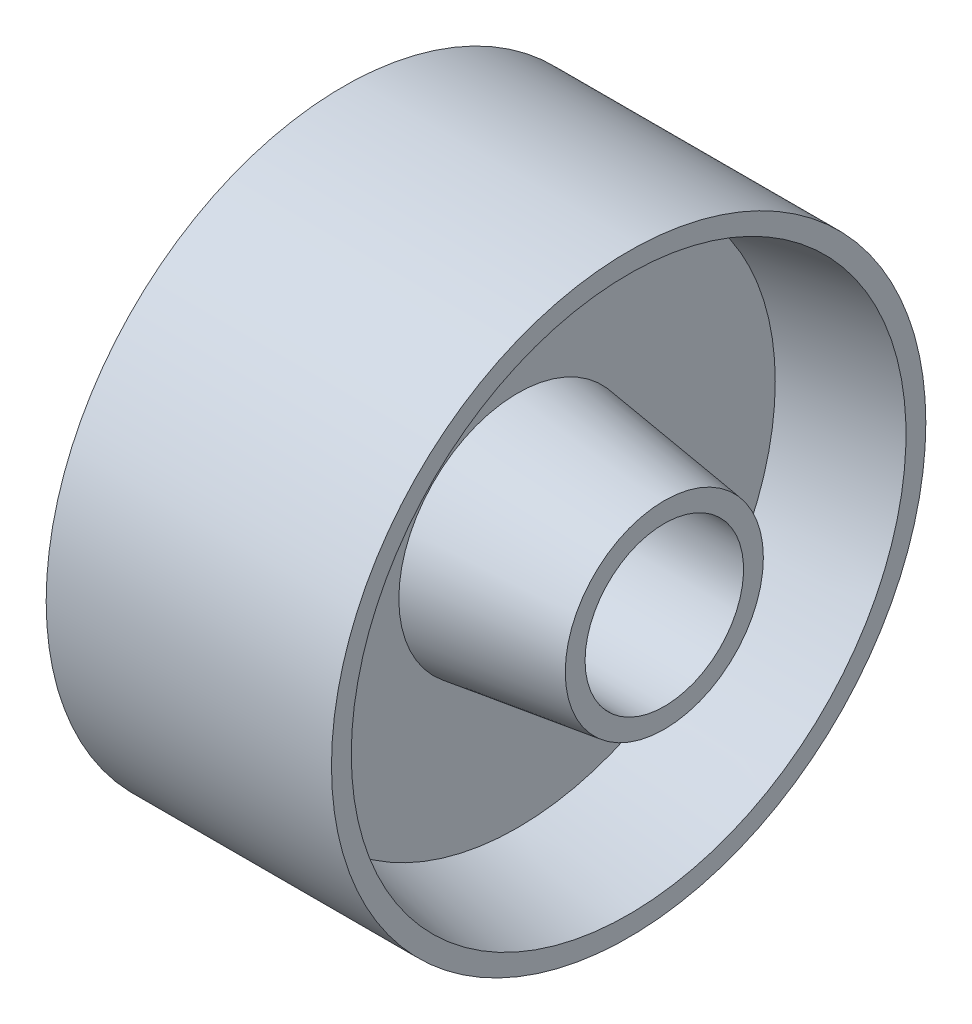
SolidWorks part; units mm, degrees
ref_plane "Front Plane" through (0, 0, 0) normal (0, 0, 1) x (1, 0, 0)
ref_plane "Top Plane" through (0, 0, 0) normal (0, 1, 0) x (1, 0, 0)
ref_plane "Right Plane" through (0, 0, 0) normal (1, 0, 0) x (0, 0, -1)
sketch "Sketch1" plane through (0, 0, 0) normal (0, 0, 1) x (1, 0, 0)
  line L16 (0, 0) -> (160.306, 0) construction
  line L18 (-36, 75) -> (36, 75)
  line L19 (36, 75) -> (36, 70)
  line L20 (36, 70) -> (8, 65)
  line L21 (8, 65) -> (8, 30)
  line L22 (8, 30) -> (45, 25)
  line L23 (45, 25) -> (45, 20)
  line L24 (45, 20) -> (-45, 20)
  line L25 (0, 75) -> (0, 20) construction
  line L26 (-8, 30) -> (-45, 25)
  line L27 (-45, 25) -> (-45, 20)
  line L28 (-8, 65) -> (-8, 30)
  line L29 (-36, 75) -> (-36, 70)
  line L30 (-36, 70) -> (-8, 65)
  dimension "D1" = 20
  dimension "D2" = 25
  dimension "D3" = 70
  dimension "D4" = 75
  dimension "D5" = 30
  dimension "D6" = 65
  dimension "D7" = 28
  dimension "D8" = 36
  dimension "D9" = 45
revolve "Revolve2" add sketch "Sketch1" angle 360 about L16
